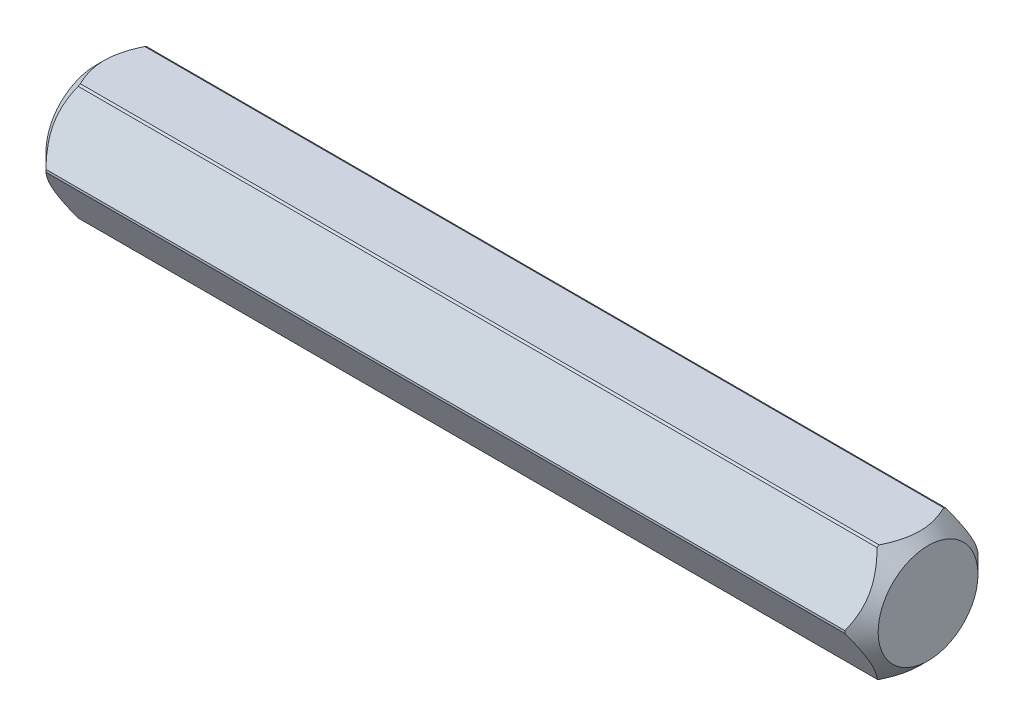
SolidWorks part; units mm, degrees
material "6061-O (SS)"
ref_plane "前视基准面" through (0, 0, 0) normal (0, 0, 1) x (1, 0, 0)
ref_plane "上视基准面" through (0, 0, 0) normal (0, 1, 0) x (1, 0, 0)
ref_plane "右视基准面" through (0, 0, 0) normal (1, 0, 0) x (0, 0, -1)
sketch "草图1" plane through (0, 0, 0) normal (1, 0, 0) x (0, 0, -1)
  line L1 (4.0415, 0) -> (2.0207, 3.5)
  line L2 (2.0207, 3.5) -> (-2.0207, 3.5)
  line L3 (-2.0207, 3.5) -> (-4.0415, 0)
  line L4 (-4.0415, 0) -> (-2.0207, -3.5)
  line L5 (-2.0207, -3.5) -> (2.0207, -3.5)
  line L6 (2.0207, -3.5) -> (4.0415, 0)
  circle A1 centre (0, 0) radius 3.5 construction
  dimension "D1" = 7
extrude "初始整轴" add sketch "草图1" along normal mid plane 50
sketch "草图8" plane through (0, 0, 0) normal (1, 0, 0) x (0, 0, -1)
  circle A0 centre (0, 0) radius 4
  circle A1 centre (0, 0) radius 5
  dimension "D1" = 8
  dimension "D2" = 1
extrude "整轴外圆" cut sketch "草图8" against normal through all both and the other way through all
sketch "草图10" plane through (0, 0, 0) normal (0, 0, 1) x (1, 0, 0)
  line L0 (25, 0) -> (-25, 0) construction
  line L7 (0, 0) -> (0, 3.4271) construction
  line L8 (-25, 3.4271) -> (25, 3.4271) construction
  line L12 (-25.5, 4) -> (-24, 4)
  line L13 (-25.5, 4) -> (-25.5, 2.5)
  line L14 (-24, 4) -> (-25.5, 2.5)
  line L15 (-25, 3.4271) -> (-25, 0.0729) construction
  line L16 (25, 3.5) -> (-25, 3.5) construction
  line L17 (24, 4) -> (25.5, 2.5)
  line L18 (25.5, 4) -> (25.5, 2.5)
  line L19 (25.5, 4) -> (24, 4)
  line L20 (-25, 0.0729) -> (-25, -0.0729) construction
  point P6 (0, 0)
  point P8 (0, 0)
  dimension "D1" = 1.5
  dimension "D2" = 1.5
  dimension "D3" = 0.5
  dimension "D4" = 0.5
revolve "初始倒角" cut sketch "草图10" angle 360 about L0
sketch "草图2" [suppressed] plane through (25, 0, 0) normal (1, 0, 0) x (0, 0, -1)
  circle A0 centre (0, 0) radius 3
  circle A1 centre (0, 0) radius 4
  dimension "D1" = 8
  dimension "右侧凸台直径" = 6
extrude "右侧凸台切除" [suppressed] cut sketch "草图2" against normal blind 5
chamfer "右侧凸台倒角" [suppressed] distance 0.3 angle 45
sketch "草图3" [suppressed] plane through (-25, 0, 0) normal (-1, 0, 0) x (0, 0, 1)
  circle A0 centre (0, 0) radius 3
  circle A1 centre (0, 0) radius 4
  dimension "D1" = 8
  dimension "左侧凸台直径" = 6
extrude "左侧凸台切除" [suppressed] cut sketch "草图3" against normal blind 5
chamfer "左侧凸台倒角" [suppressed] distance 0.3 angle 45
sketch "草图4" plane through (0, 0, 0) normal (0, 0, 1) x (1, 0, 0)
  line L0 (-13.3489, 0) -> (13.3489, 0) construction
  line L3 (14.5, 4) -> (15.5, 4)
  line L4 (14.5, 4) -> (14.5, 3.3)
  line L5 (14.5, 3.3) -> (15.5, 3.3)
  line L6 (15.5, 4) -> (15.5, 3.3)
  line L7 (15, 4) -> (15, -2.1923) construction
  point P6 (0, 0)
  dimension "D1" = 3.3
  dimension "D2" = 4
  dimension "槽1宽度" = 1
  dimension "槽1中心距离" = 15
revolve "卡簧槽1" [suppressed] cut sketch "草图4" angle 360 about L0
sketch "草图5" plane through (0, 0, 0) normal (0, 0, 1) x (1, 0, 0)
  line L0 (-10.9541, 0) -> (10.9541, 0) construction
  line L3 (-15.5, 4) -> (-14.5, 4)
  line L4 (-15.5, 4) -> (-15.5, 3.3)
  line L5 (-15.5, 3.3) -> (-14.5, 3.3)
  line L6 (-14.5, 4) -> (-14.5, 3.3)
  line L7 (-15, 4) -> (-15, -2.3192) construction
  point P6 (0, 0)
  dimension "D1" = 3.3
  dimension "D2" = 4
  dimension "槽2宽度" = 1
  dimension "槽2中心距离" = 15
revolve "卡簧槽2" [suppressed] cut sketch "草图5" angle 360 about L0
sketch "草图6" [suppressed] plane through (25, 0, 0) normal (1, 0, 0) x (0, 0, -1)
  circle A0 centre (0, 0) radius 2
  dimension "右侧攻丝直径" = 4
extrude "右侧攻丝切除" [suppressed] cut sketch "草图6" against normal blind 5
chamfer "右侧攻丝倒角" [suppressed] distance 0.5 angle 45
sketch "草图7" [suppressed] plane through (-25, 0, 0) normal (-1, 0, 0) x (0, 0, 1)
  circle A0 centre (0, 0) radius 2
  dimension "左侧攻丝直径" = 4
extrude "左侧攻丝切除" [suppressed] cut sketch "草图7" against normal blind 5
chamfer "左侧攻丝倒角" [suppressed] distance 0.5 angle 45
other "冻结***"
